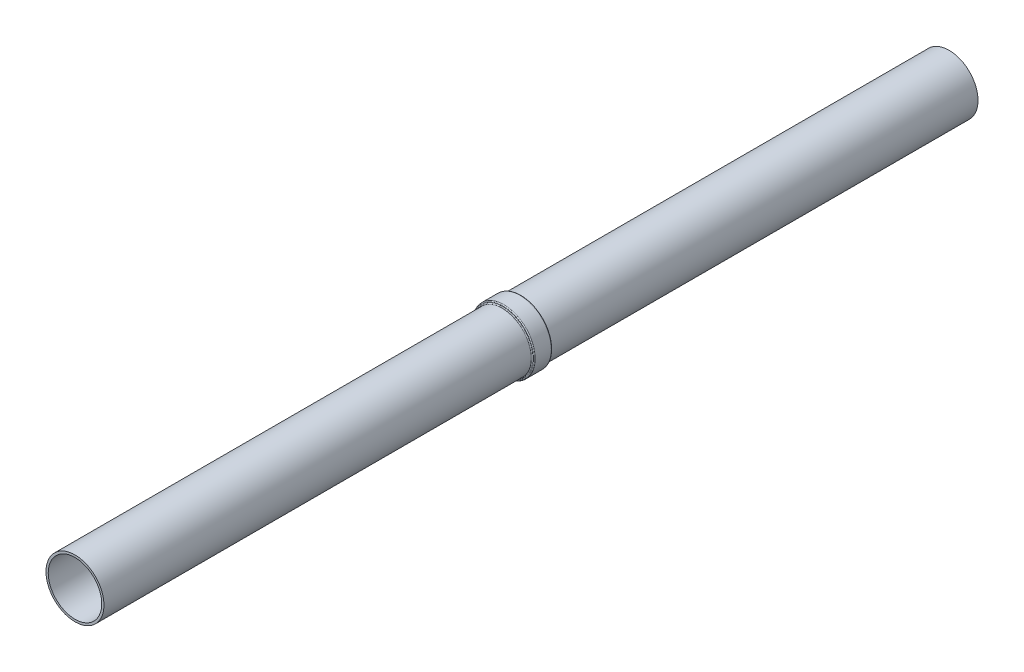
SolidWorks part; units mm, degrees
ref_plane "Front Plane" through (0, 0, 0) normal (0, 0, 1) x (1, 0, 0)
ref_plane "Top Plane" through (0, 0, 0) normal (0, 1, 0) x (1, 0, 0)
ref_plane "Right Plane" through (0, 0, 0) normal (1, 0, 0) x (0, 0, -1)
sketch "Sketch1" plane through (0, 0, 0) normal (0, 0, 1) x (1, 0, 0)
  circle A0 centre (0, 0) radius 38.1
  circle A1 centre (0, 0) radius 41.275
  dimension "D1" = 76.2
  dimension "D2" = 82.55
extrude "Boss-Extrude1" add sketch "Sketch1" along normal blind 609.6
sketch "Sketch3" plane through (0, 0, 609.6) normal (0, 0, 1) x (1, 0, 0)
  circle A0 centre (0, 0) radius 44.45
  dimension "D1" = 88.9
extrude "Boss-Extrude2" add sketch "Sketch3" along normal blind 25.4
sketch "Sketch5" plane through (0, 0, 635) normal (0, 0, 1) x (1, 0, 0)
  circle A0 centre (0, 0) radius 38.1 construction
  circle A3 centre (0, 0) radius 38.1
  circle A4 centre (0, 0) radius 41.275 construction
  circle A5 centre (0, 0) radius 41.275
extrude "Boss-Extrude4" add sketch "Sketch5" along normal blind 609.6
fillet "Fillet1" radius 1.27 4 edges at (41.275, 0, 635) (44.45, 0, 635) (44.45, 0, 609.6) (41.275, 0, 609.6)
